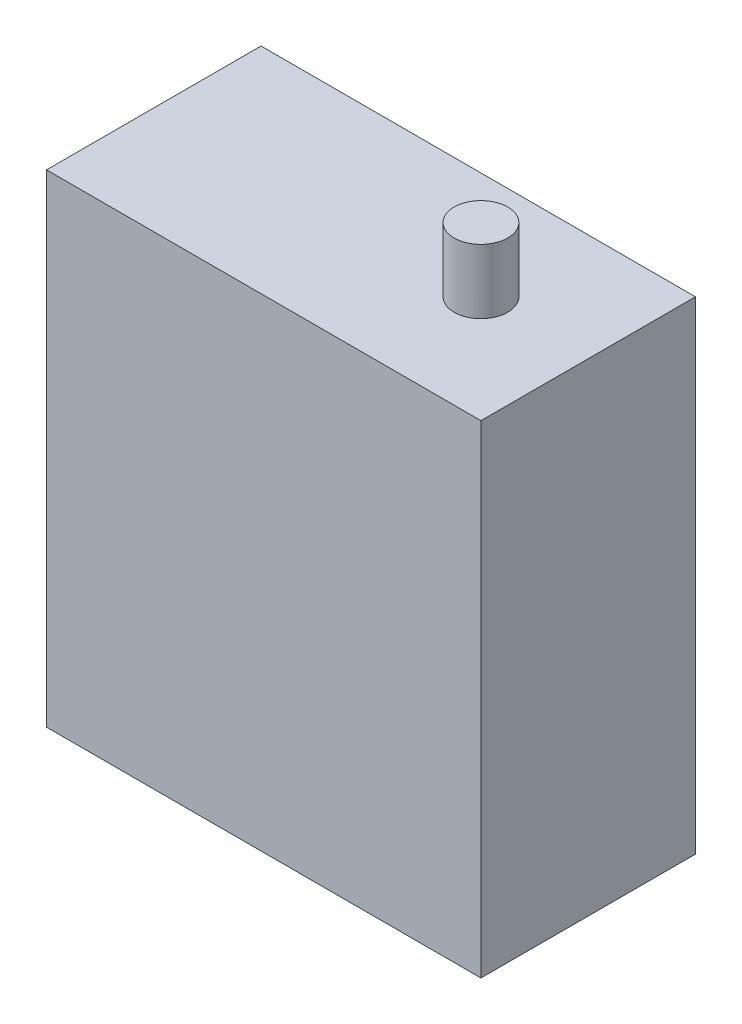
SolidWorks part; units mm, degrees
ref_plane "Front Plane" through (0, 0, 0) normal (0, 0, 1) x (1, 0, 0)
ref_plane "Top Plane" through (0, 0, 0) normal (0, 1, 0) x (1, 0, 0)
ref_plane "Right Plane" through (0, 0, 0) normal (1, 0, 0) x (0, 0, -1)
sketch "Sketch1" plane through (0, 0, 0) normal (0, 0, 1) x (1, 0, 0)
  line L1 (-20.25, 22.5) -> (20.25, 22.5)
  line L2 (-20.25, 22.5) -> (-20.25, -22.5)
  line L3 (-20.25, -22.5) -> (20.25, -22.5)
  line L4 (20.25, 22.5) -> (20.25, -22.5)
  line L5 (-20.25, 22.5) -> (20.25, -22.5) construction
  line L6 (-20.25, -22.5) -> (20.25, 22.5) construction
  point P0 (0, 0)
  dimension "D1" = 45
  dimension "D2" = 40.5
extrude "Boss-Extrude1" add sketch "Sketch1" along normal blind 20
sketch "Sketch2" plane through (0, 22.5, 0) normal (0, 1, 0) x (1, 0, 0)
  line L0 (20.25, 0) -> (-20.25, 0) construction
  line L2 (20.25, -20) -> (20.25, 0) construction
  circle A0 centre (10.25, -10) radius 2.5
  dimension "D3" = 5
  dimension "D1" = 10
  dimension "D2" = 10
extrude "Boss-Extrude2" add sketch "Sketch2" along normal blind 6
sketch "Sketch3" plane through (0, -22.5, 0) normal (0, -1, 0) x (-1, 0, 0)
  line L0 (20.25, -20) -> (-20.25, -20) construction
  circle A0 centre (0, -10) radius 2.5485
  dimension "D1" = 10
extrude "Cut-Extrude1" cut sketch "Sketch3" against normal blind 10
